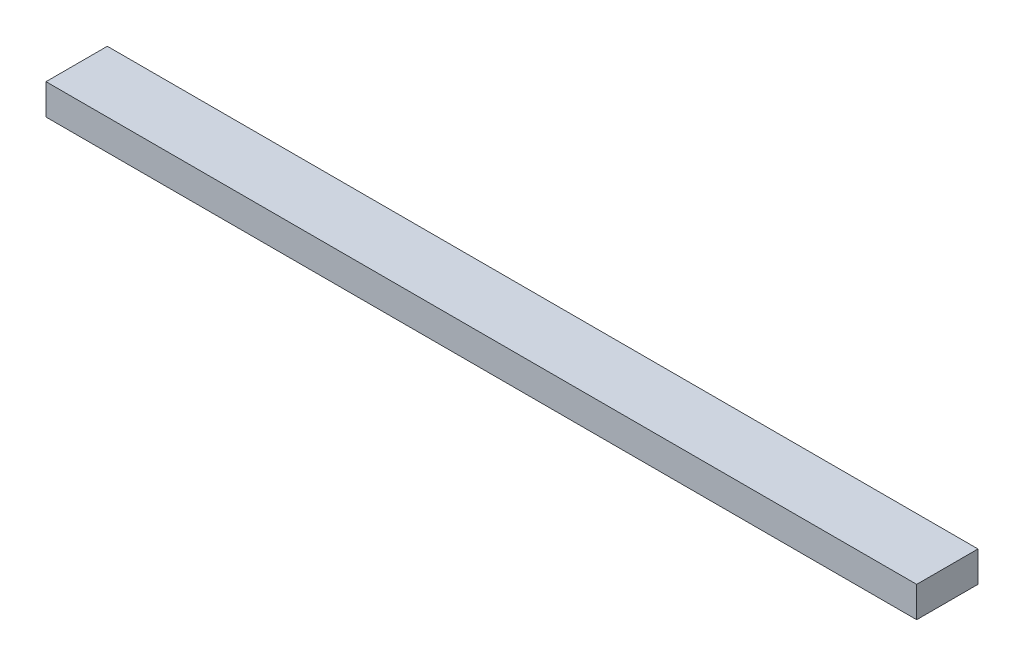
SolidWorks part; units mm, degrees
ref_plane "Front Plane" through (0, 0, 0) normal (0, 0, 1) x (1, 0, 0)
ref_plane "Top Plane" through (0, 0, 0) normal (0, 1, 0) x (1, 0, 0)
ref_plane "Right Plane" through (0, 0, 0) normal (1, 0, 0) x (0, 0, -1)
sketch "Sketch1" plane through (0, 0, 0) normal (0, 1, 0) x (1, 0, 0)
  line L1 (0, 0) -> (71, 0)
  line L2 (0, 0) -> (0, 5)
  line L3 (0, 5) -> (71, 5)
  line L4 (71, 0) -> (71, 5)
  dimension "D1" = 71
  dimension "D2" = 5
extrude "Boss-Extrude1" add sketch "Sketch1" along normal blind 2.5
